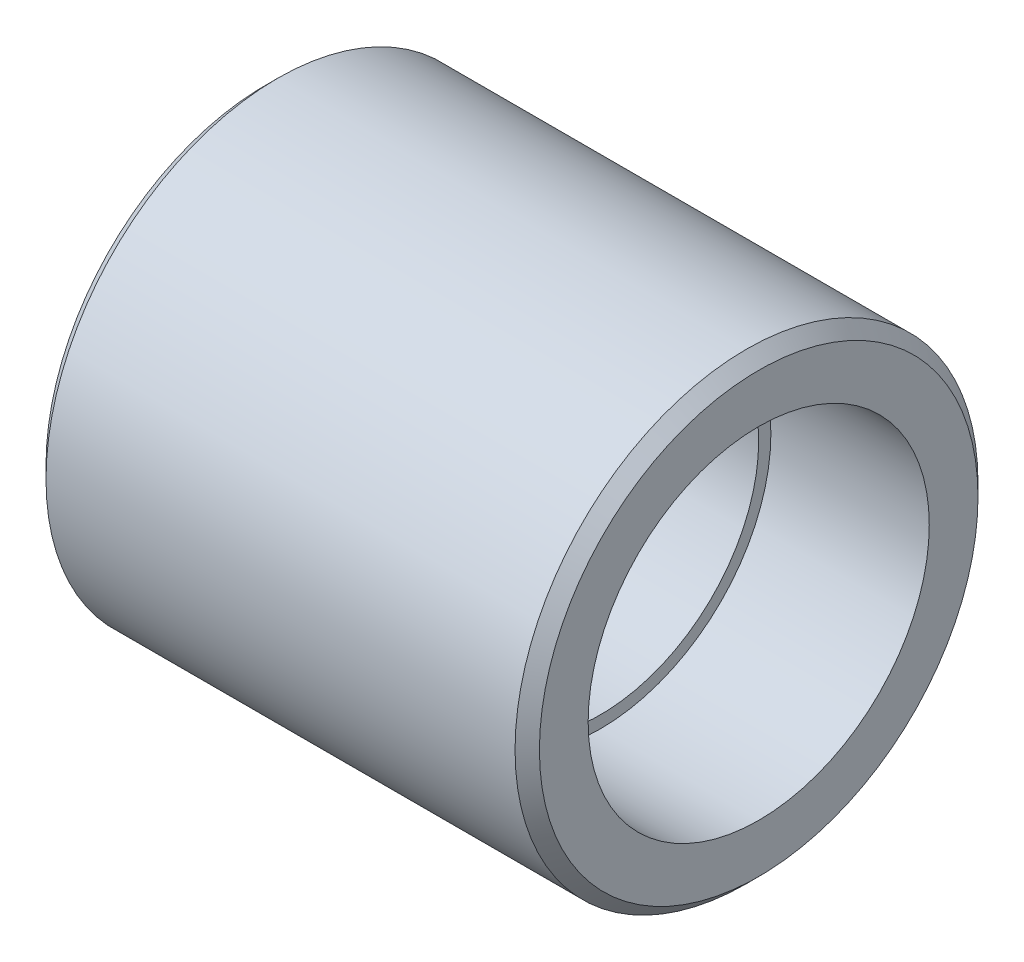
SolidWorks part; units mm, degrees
ref_plane "Plan1" through (0, 0, 0) normal (0, 0, 1) x (1, 0, 0)
ref_plane "Plan2" through (0, 0, 0) normal (0, 1, 0) x (1, 0, 0)
ref_plane "Plan3" through (0, 0, 0) normal (1, 0, 0) x (0, 0, -1)
sketch "Esquisse1" plane through (0, 0, 0) normal (0, 0, 1) x (1, 0, 0)
  line L0 (0, 0) -> (45, 0) construction
  line L1 (0, 18) -> (0, 16)
  line L2 (0, 18) -> (1, 19)
  line L3 (1, 19) -> (39.5, 19)
  line L4 (0, 16) -> (10, 16)
  line L5 (39.5, 19) -> (40.5, 18)
  line L6 (40.5, 18) -> (40.5, 14)
  line L7 (40.5, 14) -> (27.5, 14)
  line L8 (27.5, 14) -> (27.5, 13)
  line L9 (27.5, 13) -> (10, 13)
  line L10 (10, 13) -> (10, 16)
  dimension "D1" = 45
  dimension "D2" = 1
  dimension "D3" = 32
  dimension "D4" = 38
  dimension "D5" = 45
  dimension "D6" = 1
  dimension "D7" = 40.5
  dimension "D8" = 28
  dimension "D9" = 10
  dimension "D10" = 13
  dimension "D11" = 26
revolve "Base-Révolution" add sketch "Esquisse1" angle 360 about L0
